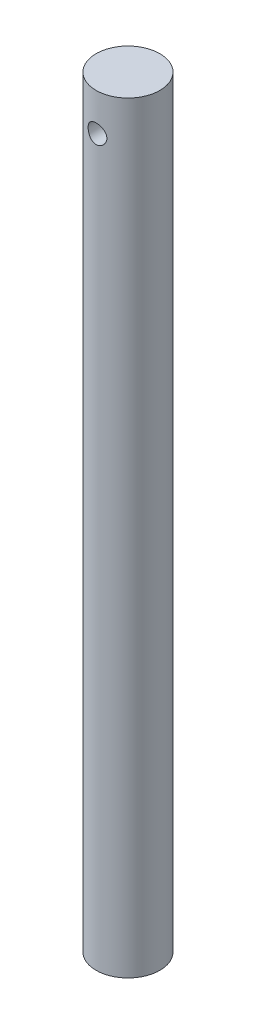
SolidWorks part; units mm, degrees
ref_plane "Front Plane" through (0, 0, 0) normal (0, 0, 1) x (1, 0, 0)
ref_plane "Top Plane" through (0, 0, 0) normal (0, 1, 0) x (1, 0, 0)
ref_plane "Right Plane" through (0, 0, 0) normal (1, 0, 0) x (0, 0, -1)
sketch "Sketch1" plane through (0, 0, 0) normal (0, 1, 0) x (1, 0, 0)
  circle A0 centre (0, 0) radius 8.5
  dimension "D1" = 17
extrude "Boss-Extrude1" add sketch "Sketch1" along normal blind 203.2
sketch "Sketch3" plane through (0, 203.2, 0) normal (0, 1, 0) x (1, 0, 0)
  circle A0 centre (0, 0) radius 8.5
  circle A1 centre (0, 0) radius 8.5 construction
ref_plane "Plane1" through (0, 0, 8.5) normal (0, 0, 1) x (1, 0, 0)
sketch "Sketch4" plane through (0, 0, 8.5) normal (0, 0, 1) x (1, 0, 0)
  line L0 (0, 203.2) -> (0, 193.2) construction
  line L1 (8.5, 203.2) -> (-8.5, 203.2) construction
  circle A0 centre (0, 193.2) radius 2.5
  point P4 (0, 0)
  point P7 (0, 0)
  dimension "D1" = 5
  dimension "D2" = 10
extrude "Cut-Extrude1" cut sketch "Sketch4" against normal through all both and the other way through all
